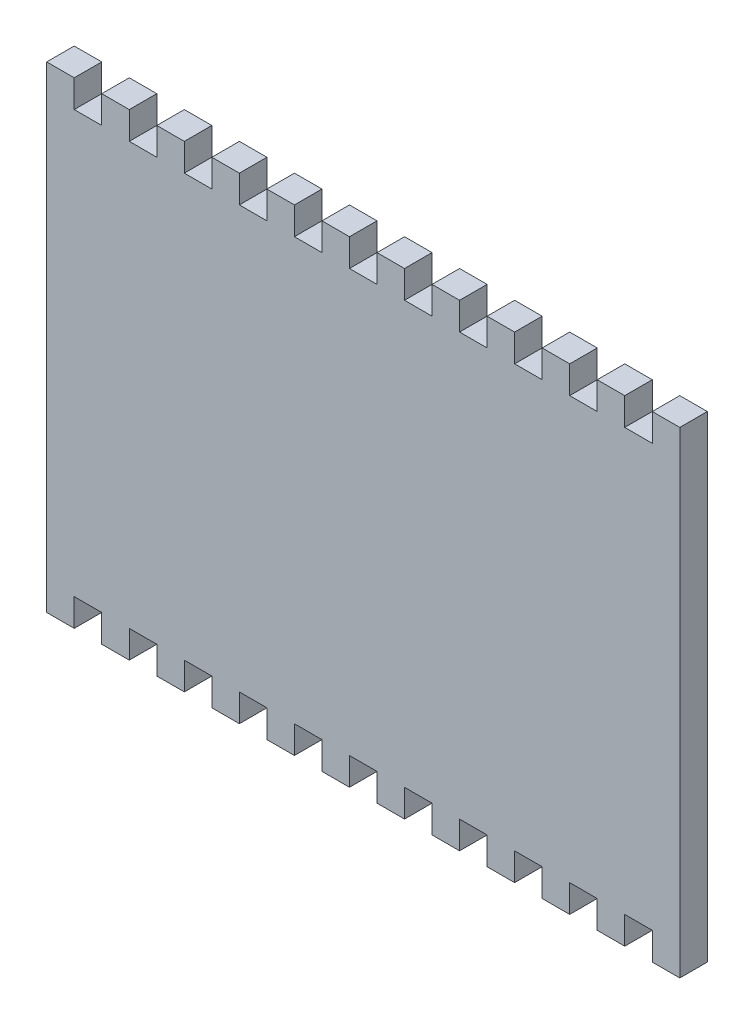
SolidWorks part; units mm, degrees
ref_plane "Front Plane" through (0, 0, 0) normal (0, 0, 1) x (1, 0, 0)
ref_plane "Top Plane" through (0, 0, 0) normal (0, 1, 0) x (1, 0, 0)
ref_plane "Right Plane" through (0, 0, 0) normal (1, 0, 0) x (0, 0, -1)
sketch "Sketch1" plane through (0, 0, 0) normal (0, 0, 1) x (1, 0, 0)
  line L1 (75, -27.5) -> (-75, -27.5)
  line L2 (75, -27.5) -> (75, 27.5)
  line L3 (75, 27.5) -> (-75, 27.5)
  line L4 (-75, -27.5) -> (-75, 27.5)
  line L5 (75, -27.5) -> (-75, 27.5) construction
  line L6 (75, 27.5) -> (-75, -27.5) construction
  point P0 (0, 0)
  dimension "D1" = 150
  dimension "D2" = 55
extrude "Boss-Extrude1" add sketch "Sketch1" along normal blind 3.175
sketch "Sketch2" plane through (0, 0, 0) normal (0, 0, -1) x (-1, 0, 0)
  line L0 (-75, 27.5) -> (75, 27.5) construction
  line L1 (-1.5875, 30.675) -> (1.5875, 30.675)
  line L2 (-1.5875, 30.675) -> (-1.5875, 24.325)
  line L3 (-1.5875, 24.325) -> (1.5875, 24.325)
  line L4 (1.5875, 30.675) -> (1.5875, 24.325)
  line L5 (-1.5875, 30.675) -> (1.5875, 24.325) construction
  line L6 (-1.5875, 24.325) -> (1.5875, 30.675) construction
  point P0 (0, 27.5)
  dimension "D1" = 3.175
  dimension "D2" = 6.35
extrude "Cut-Extrude1" cut sketch "Sketch2" against normal up to next
pattern_linear "LPattern1" count 12 spacing 6.35 along (1, 0, 0) count 12 spacing 6.35 along (-1, 0, 0) of "Cut-Extrude1"
mirror "Mirror1" about plane through (0, 0, 0) normal (0, 1, 0) of "LPattern1", "Cut-Extrude1"
sketch "Sketch3" plane through (0, 0, 0) normal (0, 0, -1) x (-1, 0, 0)
  line L0 (-52.3875, -27.5) -> (-55.5625, -27.5) construction
  line L1 (-75, 27.5) -> (-55.5625, 27.5)
  line L2 (-75, 27.5) -> (-75, -27.5)
  line L3 (-75, -27.5) -> (-55.5625, -27.5)
  line L4 (-55.5625, 27.5) -> (-55.5625, -27.5)
  line L5 (-55.5625, -24.325) -> (-55.5625, -27.5) construction
  line L7 (75, 27.5) -> (55.5625, 27.5)
  line L8 (75, 27.5) -> (75, -27.5)
  line L9 (75, -27.5) -> (55.5625, -27.5)
  line L10 (55.5625, 27.5) -> (55.5625, -27.5)
extrude "Cut-Extrude2" cut sketch "Sketch3" against normal blind 10
sketch "Sketch5" plane through (0, 0, 0) normal (0, 0, -1) x (-1, 0, 0)
  line L1 (-55.5625, 27.5) -> (-42.8625, 27.5)
  line L2 (-55.5625, 27.5) -> (-55.5625, 24.325)
  line L3 (-55.5625, 24.325) -> (-42.8625, 24.325)
  line L5 (55.5625, 27.5) -> (42.8625, 27.5)
  line L6 (55.5625, 27.5) -> (55.5625, 24.325)
  line L7 (55.5625, 24.325) -> (42.8625, 24.325)
  line L9 (-42.8625, 24.325) -> (-39.6875, 24.325)
  line L11 (-42.8625, 27.5) -> (-39.6875, 27.5)
  line L12 (-39.6875, 24.325) -> (-39.6875, 27.5)
  line L13 (39.6875, 27.5) -> (42.8625, 27.5)
  line L14 (39.6875, 27.5) -> (39.6875, 24.325)
  line L15 (39.6875, 24.325) -> (42.8625, 24.325)
extrude "Cut-Extrude3" cut sketch "Sketch5" against normal blind 10
sketch "Sketch6" plane through (0, 0, 0) normal (0, 0, -1) x (-1, 0, 0)
  line L1 (-55.5625, -27.5) -> (-39.6875, -27.5)
  line L2 (-55.5625, -27.5) -> (-55.5625, -24.325)
  line L3 (-55.5625, -24.325) -> (-39.6875, -24.325)
  line L4 (-39.6875, -27.5) -> (-39.6875, -24.325)
  line L5 (55.5625, -27.5) -> (39.6875, -27.5)
  line L6 (55.5625, -27.5) -> (55.5625, -24.325)
  line L7 (55.5625, -24.325) -> (39.6875, -24.325)
  line L8 (39.6875, -27.5) -> (39.6875, -24.325)
extrude "Cut-Extrude4" cut sketch "Sketch6" against normal blind 10
sketch "Sketch7" plane through (0, 0, 0) normal (0, 0, -1) x (-1, 0, 0)
  line L1 (-55.5625, 24.325) -> (-36.5125, 24.325)
  line L2 (-55.5625, 24.325) -> (-55.5625, -24.325)
  line L3 (-55.5625, -24.325) -> (-36.5125, -24.325)
  line L4 (-36.5125, 24.325) -> (-36.5125, -24.325)
  line L5 (55.5625, 24.325) -> (36.5125, 24.325)
  line L6 (55.5625, 24.325) -> (55.5625, -24.325)
  line L7 (55.5625, -24.325) -> (36.5125, -24.325)
  line L8 (36.5125, 24.325) -> (36.5125, -24.325)
extrude "Cut-Extrude5" cut sketch "Sketch7" against normal blind 10
sketch "Sketch8" plane through (0, 0, 0) normal (0, 0, -1) x (-1, 0, 0)
  line L0 (-43.6255, 7.675) -> (43.6255, 7.675) construction
  line L1 (-1.5875, -24.325) -> (1.5875, -24.325) construction
  point P3 (0, 7.675)
  dimension "D1" = 32
sketch "Sketch9" plane through (0, 0, 0) normal (0, 0, -1) x (-1, 0, 0)
  line L0 (-200043.6255, 7.675) -> (200043.6255, 7.675) construction
  line L1 (-1.5875, 7.675) -> (1.5875, 7.675)
  line L2 (-1.5875, 7.675) -> (-1.5875, 10.85)
  line L3 (-1.5875, 10.85) -> (1.5875, 10.85)
  line L4 (1.5875, 7.675) -> (1.5875, 10.85)
  dimension "D1" = 3.175
  dimension "D2" = 3.175
  dimension "D3" = 1.5875
extrude "Cut-Extrude6" [suppressed] cut sketch "Sketch9" against normal blind 10
pattern_linear "LPattern2" [suppressed] count 3 spacing 6.35 count 3 spacing 6.35
